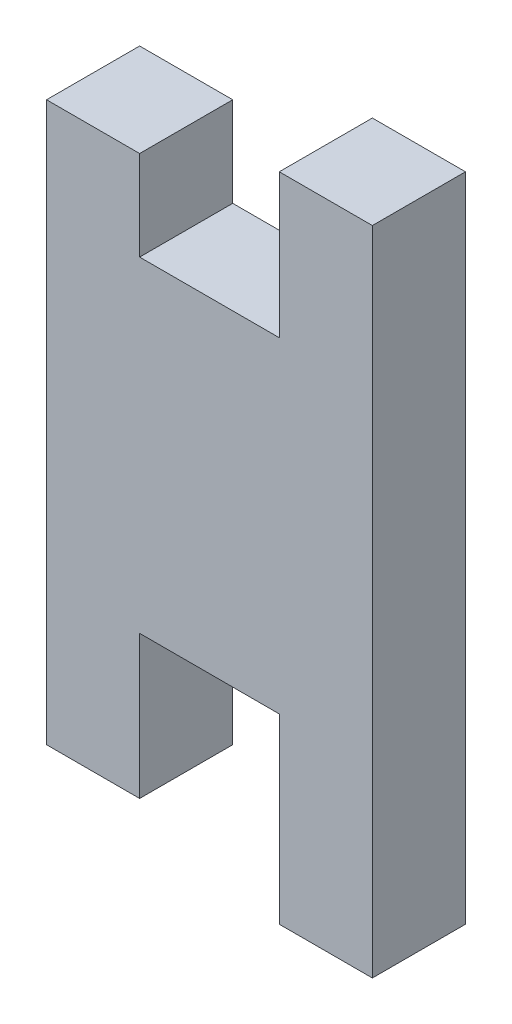
SolidWorks part; units mm, degrees
material "PLA imprimante 3D"
ref_plane "Plan de face" through (0, 0, 0) normal (0, 0, 1) x (1, 0, 0)
ref_plane "Plan de dessus" through (0, 0, 0) normal (0, 1, 0) x (1, 0, 0)
ref_plane "Plan de droite" through (0, 0, 0) normal (1, 0, 0) x (0, 0, -1)
sketch "Esquisse3" plane through (0, 0, 0) normal (0, 0, 1) x (1, 0, 0)
  line L0 (0, 0) -> (10, 0)
  line L1 (10, 0) -> (10, -9.6367)
  line L2 (10, -9.6367) -> (25, -9.6367)
  line L3 (25, -9.6367) -> (25, 5.7998)
  line L4 (25, 5.7998) -> (35, 5.7998)
  line L5 (35, 5.7998) -> (35, -64.2002)
  line L6 (35, -64.2002) -> (25, -64.2002)
  line L7 (25, -64.2002) -> (25, -44.6367)
  line L8 (25, -44.6367) -> (10, -44.6367)
  line L9 (10, -44.6367) -> (10, -60)
  line L10 (10, -60) -> (0, -60)
  line L11 (0, -60) -> (0, 0)
  dimension "D1" = 60
  dimension "D2" = 35
  dimension "D3" = 10
  dimension "D4" = 10
  dimension "D5" = 15
  dimension "D6" = 15
  dimension "D7" = 10
  dimension "D8" = 70
extrude "Boss.-Extru.2" add sketch "Esquisse3" against normal blind 10
